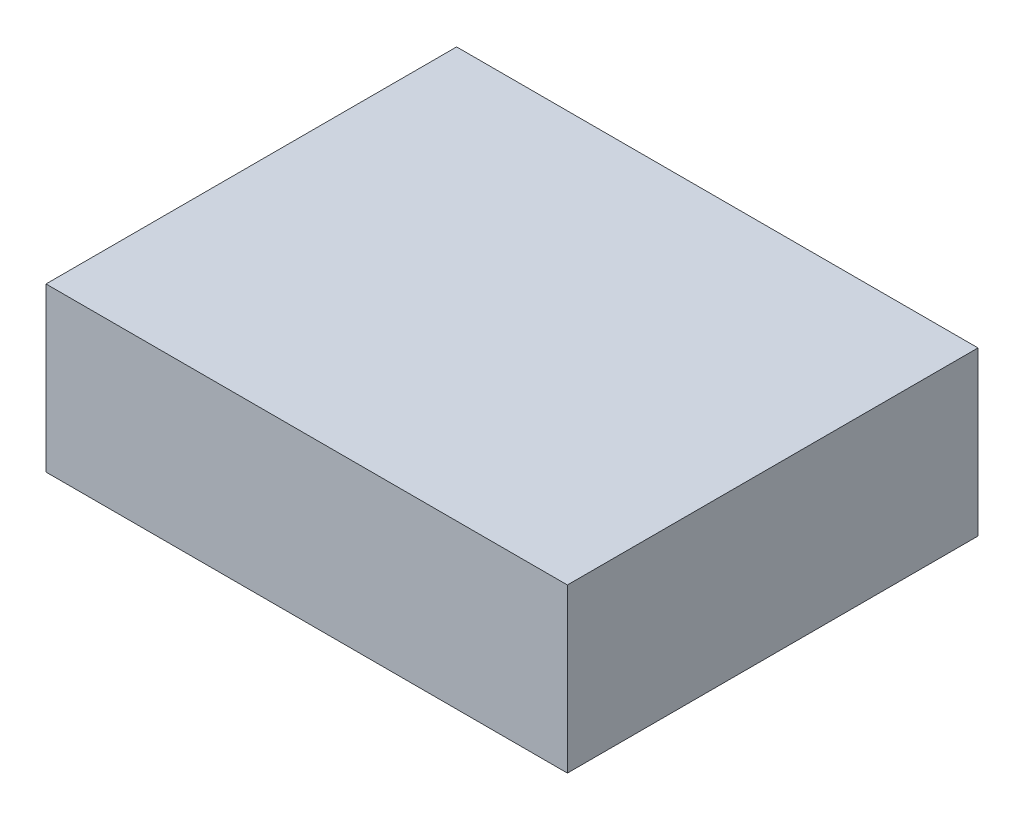
SolidWorks part; units mm, degrees
ref_plane "前视基准面" through (0, 0, 0) normal (0, 0, 1) x (1, 0, 0)
ref_plane "上视基准面" through (0, 0, 0) normal (0, 1, 0) x (1, 0, 0)
ref_plane "右视基准面" through (0, 0, 0) normal (1, 0, 0) x (0, 0, -1)
other "Configuration Table"
sketch "草图2" plane through (0, 0, 0) normal (0, 1, 0) x (1, 0, 0)
  line L1 (0, 0) -> (80, 0)
  line L2 (0, 0) -> (0, 63)
  line L3 (0, 63) -> (80, 63)
  line L4 (80, 0) -> (80, 63)
  dimension "D1" = 80
  dimension "D2" = 63
extrude "凸台-拉伸1" add sketch "草图2" along normal blind 25 contours L3 L4 L1 L2
